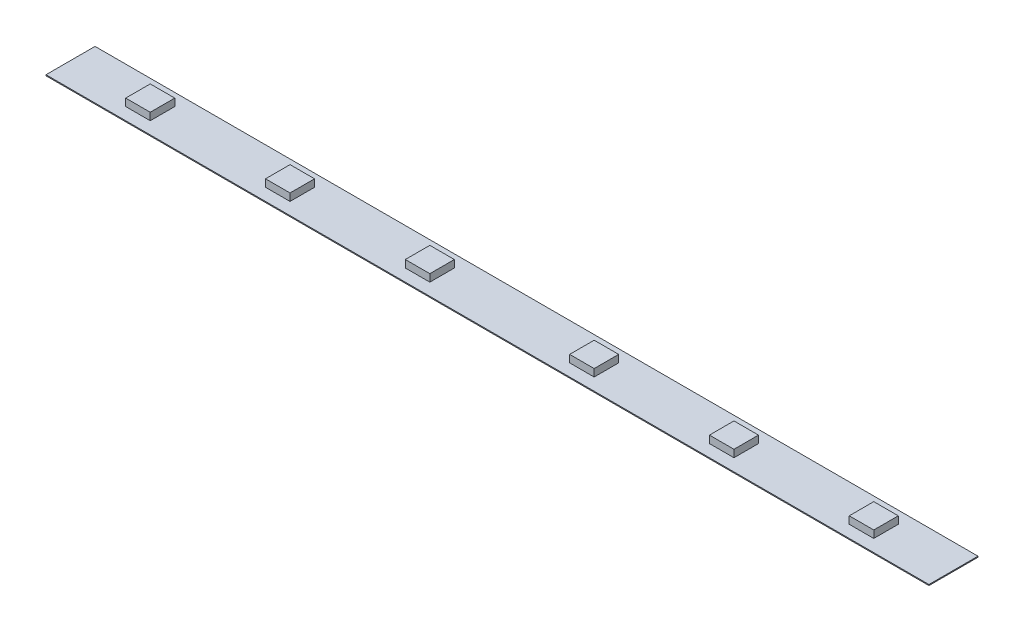
SolidWorks part; units mm, degrees
ref_plane "Plan de face" through (0, 0, 0) normal (0, 0, 1) x (1, 0, 0)
ref_plane "Plan de dessus" through (0, 0, 0) normal (0, 1, 0) x (1, 0, 0)
ref_plane "Plan de droite" through (0, 0, 0) normal (1, 0, 0) x (0, 0, -1)
sketch "Esquisse1" plane through (0, 0, 0) normal (0, 1, 0) x (1, 0, 0)
  line L1 (-90, -5) -> (90, -5)
  line L2 (-90, -5) -> (-90, 5)
  line L3 (-90, 5) -> (90, 5)
  line L4 (90, -5) -> (90, 5)
  line L5 (-90, -5) -> (90, 5) construction
  line L6 (-90, 5) -> (90, -5) construction
  point P0 (0, 0)
  dimension "D1" = 10
  dimension "D2" = 180
extrude "Boss.-Extru.1" add sketch "Esquisse1" along normal blind 0.2
sketch "Esquisse3" plane through (0, 0.2, 0) normal (0, 1, 0) x (1, 0, 0)
  line L0 (42.75, 2.5) -> (47.75, 2.5)
  line L1 (14.25, 2.5) -> (19.25, 2.5)
  line L2 (14.25, 2.5) -> (14.25, -2.5)
  line L3 (14.25, -2.5) -> (19.25, -2.5)
  line L4 (19.25, 2.5) -> (19.25, -2.5)
  line L5 (14.25, 2.5) -> (19.25, -2.5) construction
  line L6 (14.25, -2.5) -> (19.25, 2.5) construction
  line L7 (42.75, 2.5) -> (42.75, -2.5)
  line L8 (42.75, -2.5) -> (47.75, -2.5)
  line L9 (47.75, 2.5) -> (47.75, -2.5)
  line L10 (71.25, 2.5) -> (76.25, 2.5)
  line L11 (71.25, 2.5) -> (71.25, -2.5)
  line L12 (71.25, -2.5) -> (76.25, -2.5)
  line L13 (76.25, 2.5) -> (76.25, -2.5)
  line L14 (0, -0.11) -> (0, 0.11) construction
  line L15 (-14.25, -2.5) -> (-19.25, 2.5) construction
  line L16 (-14.25, 2.5) -> (-19.25, -2.5) construction
  line L17 (-76.25, 2.5) -> (-76.25, -2.5)
  line L18 (-71.25, -2.5) -> (-76.25, -2.5)
  line L19 (-71.25, 2.5) -> (-71.25, -2.5)
  line L20 (-71.25, 2.5) -> (-76.25, 2.5)
  line L21 (-47.75, 2.5) -> (-47.75, -2.5)
  line L22 (-42.75, -2.5) -> (-47.75, -2.5)
  line L23 (-42.75, 2.5) -> (-42.75, -2.5)
  line L24 (-19.25, 2.5) -> (-19.25, -2.5)
  line L25 (-14.25, -2.5) -> (-19.25, -2.5)
  line L26 (-14.25, 2.5) -> (-14.25, -2.5)
  line L27 (-14.25, 2.5) -> (-19.25, 2.5)
  line L28 (-42.75, 2.5) -> (-47.75, 2.5)
  point P0 (16.75, 0)
  point P28 (-16.75, 0)
  dimension "D1" = 5
  dimension "D2" = 14.25
  dimension "D3" = 3
extrude "Boss.-Extru.2" add sketch "Esquisse3" along normal blind 1.5
